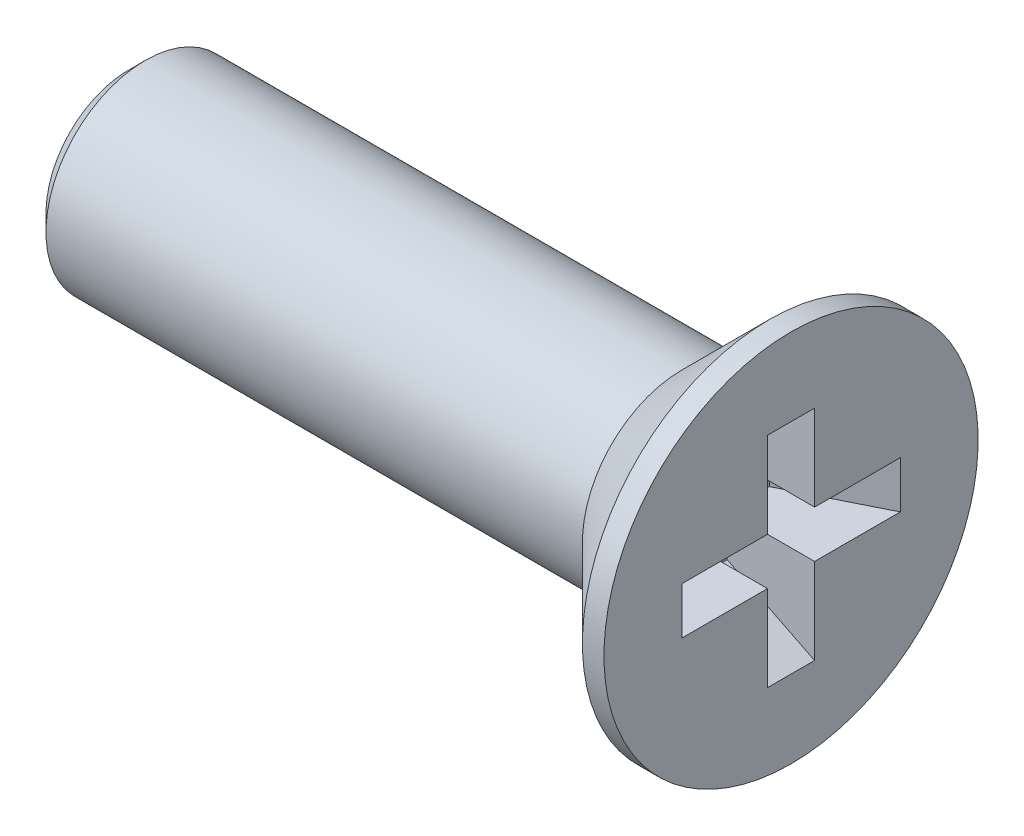
SolidWorks part; units mm, degrees
material "AISI 1020"
ref_plane "Front Plane" through (0, 0, 0) normal (0, 0, 1) x (1, 0, 0)
ref_plane "Top Plane" through (0, 0, 0) normal (0, 1, 0) x (1, 0, 0)
ref_plane "Right Plane" through (0, 0, 0) normal (1, 0, 0) x (0, 0, -1)
sketch "Sketch1" plane through (0, 0, 0) normal (0, 0, 1) x (1, 0, 0)
  line L0 (0, 0) -> (-20, 0) construction
  line L1 (0, 0) -> (0, 5.65)
  line L2 (0, 5.65) -> (-0.65, 5.65)
  line L3 (-0.65, 5.65) -> (-3.3, 3)
  line L4 (-3.3, 3) -> (-20, 3)
  line L5 (-20, 3) -> (-20, 0)
  line L6 (0, 0) -> (-20, 0)
  dimension "Diam" = 6
  dimension "G_diam" = 11.3
  dimension "D3" = 45
  dimension "G_plotis" = 3.3
  dimension "Ilgis" = 20
revolve "Revolve1" add sketch "Sketch1" angle 360 about L0
cosmetic thread "Cosmetic Thread1" parameters "Sr_ilgis"=16.7, "Sr_diam"=5
sketch "Sketch2" plane through (0, 0, 0) normal (1, 0, 0) x (0, 0, -1)
  line L0 (-3.3, -0.71) -> (3.3, 0.71) construction
  line L1 (-3.3, 0.71) -> (3.3, 0.71)
  line L2 (-3.3, 0.71) -> (-3.3, -0.71)
  line L3 (-3.3, -0.71) -> (3.3, -0.71)
  line L4 (3.3, 0.71) -> (3.3, -0.71)
  line L5 (-0.71, 3.3) -> (0.71, 3.3)
  line L6 (-0.71, 3.3) -> (-0.71, -3.3)
  line L7 (-0.71, -3.3) -> (0.71, -3.3)
  line L8 (0.71, 3.3) -> (0.71, -3.3)
  line L9 (-0.71, -3.3) -> (0.71, 3.3) construction
  dimension "Y_plotis" = 1.42
  dimension "Y_diam" = 6.6
extrude "Cut-Extrude1" cut sketch "Sketch2" against normal blind 2.64 contours L8 L5 L6 L1 | L6 L1 L2 L3 | L8 L1 L6 L3 | L1 L8 L3 L4 | L8 L3 L6 L7
draft "Draft1" type of draft neutral plane draft angle 26.5 faces to draft 4 face at (-1.32, 0, -3.3) face at (-1.32, -3.3, 0) face at (-1.32, 0, 3.3) face at (-1.32, 3.3, 0) neutral plane through (0, 0, 0) neutral plane normal (1, 0, 0) parameters "D1"=26.5
chamfer "Chamfer1" distance 0.5 angle 45 1 edges at (-20, 3, 0)
